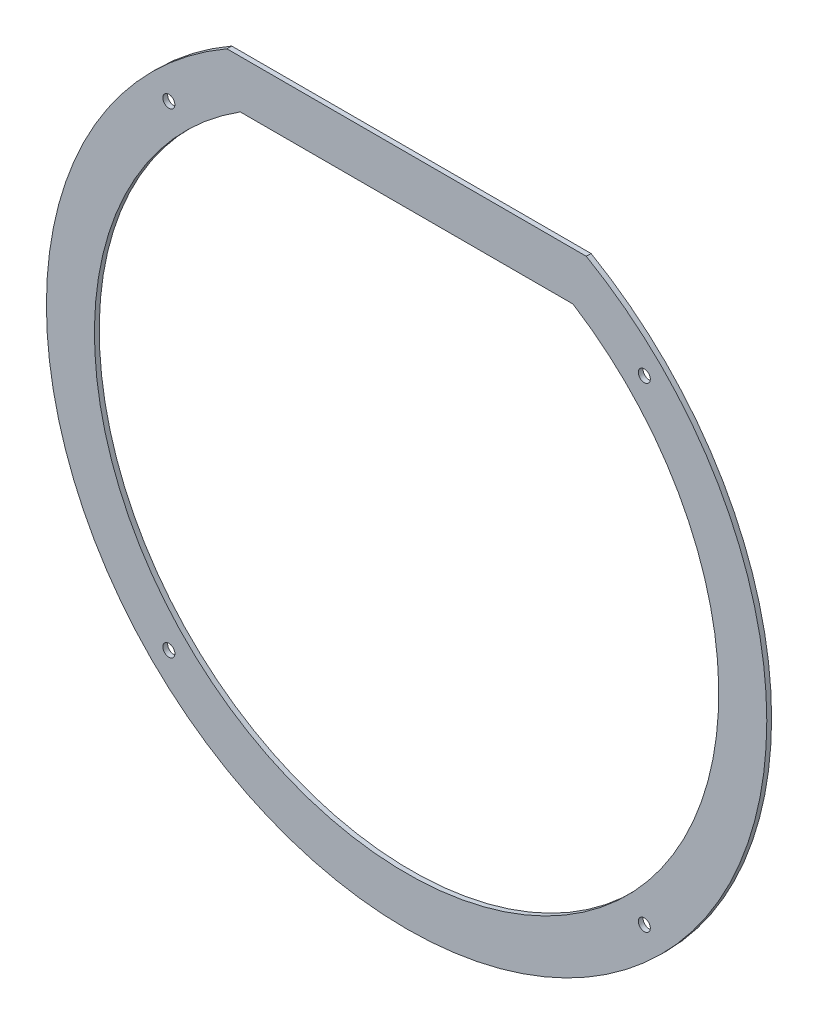
SolidWorks part; units mm, degrees
ref_plane "Face" through (0, 0, 0) normal (0, 0, 1) x (1, 0, 0)
ref_plane "Dessus" through (0, 0, 0) normal (0, 1, 0) x (1, 0, 0)
ref_plane "Droite" through (0, 0, 0) normal (1, 0, 0) x (0, 0, -1)
sketch "Esquisse1" plane through (0, 0, 0) normal (0, 0, 1) x (1, 0, 0)
  line L0 (-74.8331, 130) -> (74.8331, 130)
  line L1 (140, 0) -> (-140, 0) construction
  line L2 (-69.282, 110) -> (69.282, 110)
  line L3 (98.9949, 98.9949) -> (-98.9949, -98.9949) construction
  line L4 (-98.9949, 98.9949) -> (98.9949, -98.9949) construction
  arc A0 (-74.8331, 130) -> (74.8331, 130) centre (0, 0) ccw
  arc A1 (-69.282, 110) -> (69.282, 110) centre (0, 0) ccw
  circle A2 centre (0, 0) radius 140 construction
  circle A3 centre (-98.9949, 98.9949) radius 2.5
  circle A4 centre (-98.9949, -98.9949) radius 2.5
  circle A5 centre (98.9949, -98.9949) radius 2.5
  circle A6 centre (98.9949, 98.9949) radius 2.5
  dimension "D1" = 300
  dimension "D2" = 20
  dimension "D3" = 10
  dimension "D4" = 130
  dimension "D8" = 5
  dimension "D9" = 5
  dimension "D10" = 5
  dimension "D11" = 5
  dimension "D5" = 45
  dimension "D6" = 20
  dimension "D7" = 45
extrude "Boss.-Extru.1" add sketch "Esquisse1" along normal blind 2
